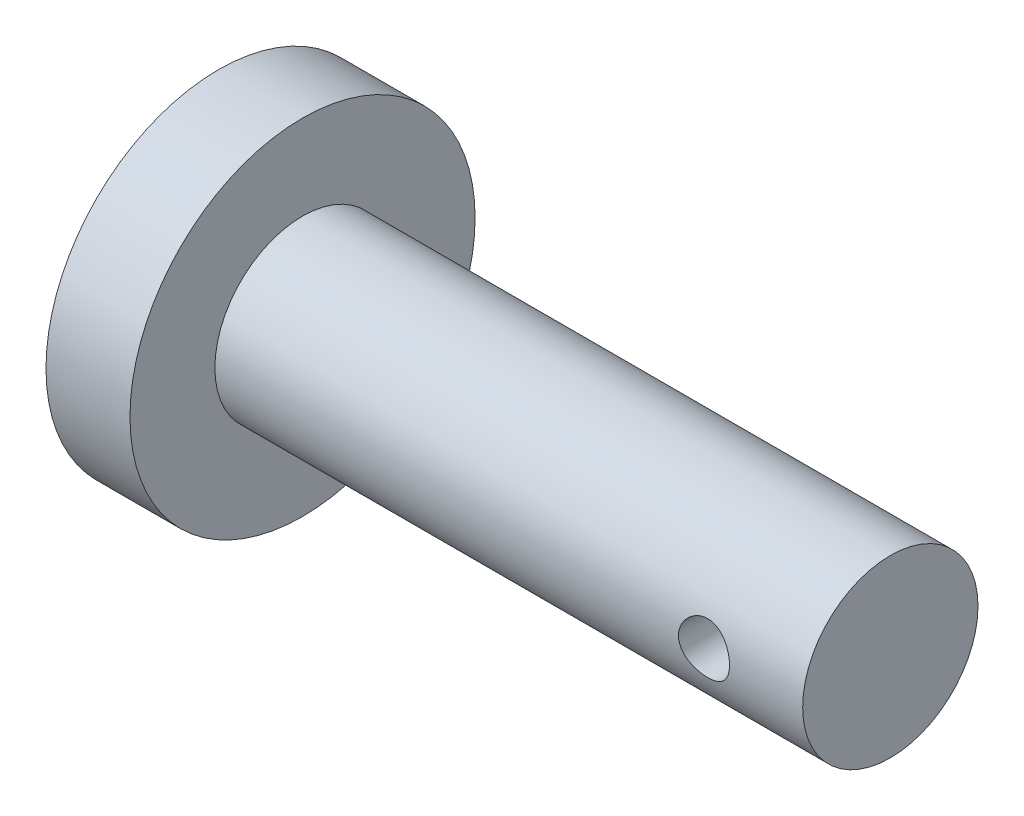
SolidWorks part; units mm, degrees
ref_plane "Front Plane" through (0, 0, 0) normal (0, 0, 1) x (1, 0, 0)
ref_plane "Top Plane" through (0, 0, 0) normal (0, 1, 0) x (1, 0, 0)
ref_plane "Right Plane" through (0, 0, 0) normal (1, 0, 0) x (0, 0, -1)
sketch "Sketch1" plane through (0, 0, 0) normal (0, 0, 1) x (1, 0, 0)
  line L0 (-70.7037, 35.0241) -> (-53.6599, 35.0241)
  line L1 (-53.6599, 35.0241) -> (-53.6599, 17.793)
  line L2 (-53.6599, 17.793) -> (65.6467, 17.793)
  line L3 (-70.7037, 0) -> (65.6467, 0)
  line L4 (65.6467, 0) -> (65.6467, 17.793)
  line L5 (-70.7037, 35.0241) -> (-70.7037, 0)
revolve "Revolve2" add sketch "Sketch1" angle 360 about L3
sketch "Sketch2" plane through (0, 0, 0) normal (0, 0, 1) x (1, 0, 0)
  line L0 (-70.7037, 0) -> (65.6467, 0) construction
  circle A0 centre (45.6112, 0) radius 5.1834
extrude "Cut-Extrude1" cut sketch "Sketch2" against normal through all both and the other way through all
